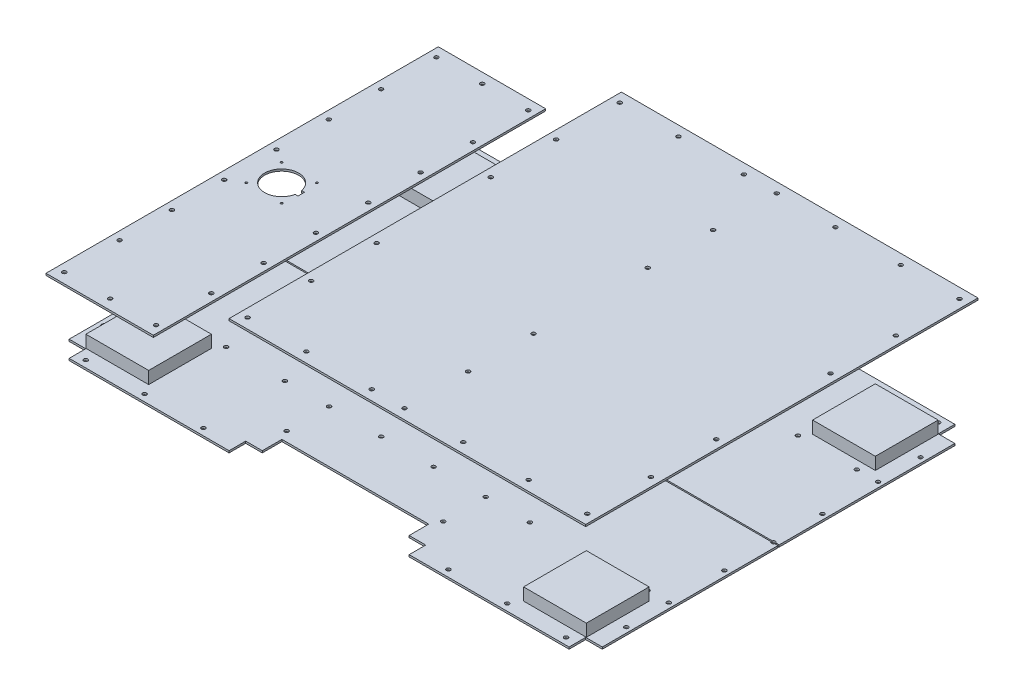
SolidWorks part; units mm, degrees
material "1060 Alloy"
ref_plane "Front Plane" through (0, 0, 0) normal (0, 0, 1) x (1, 0, 0)
ref_plane "Top Plane" through (0, 0, 0) normal (0, 1, 0) x (1, 0, 0)
ref_plane "Right Plane" through (0, 0, 0) normal (1, 0, 0) x (0, 0, -1)
sketch "Sketch2" plane through (0, 422.0595, 0) normal (0, 1, 0) x (1, 0, 0)
  line L0 (436.2951, -933.6952) -> (410.8951, -933.6952) construction
  line L9 (436.2951, -933.6952) -> (410.8951, -933.6952) construction
  line L11 (196.2951, -933.6952) -> (196.2951, -903.6952) construction
  line L19 (196.2951, -834.4952) -> (196.2951, -933.6952) construction
  line L21 (196.2951, -903.6952) -> (410.8951, -903.6952) construction
  line L22 (410.8951, -933.6952) -> (410.8951, -834.4952) construction
  line L72 (410.8951, -903.6952) -> (410.8951, -933.6952) construction
  line L73 (436.2951, -959.0952) -> (436.2951, -933.6952) construction
  line L76 (690.8951, -959.0952) -> (436.2951, -959.0952) construction
  line L78 (690.8951, -933.6952) -> (690.8951, -959.0952) construction
  line L79 (410.8951, -384.4952) -> (436.2951, -384.4952) construction
  line L80 (436.2951, -384.4952) -> (436.2951, -359.0952) construction
  line L81 (436.2951, -359.0952) -> (690.8951, -359.0952) construction
  line L82 (436.2951, -959.0952) -> (436.2951, -933.6952) construction
  line L83 (690.8951, -959.0952) -> (436.2951, -959.0952) construction
  line L84 (690.8951, -933.6952) -> (690.8951, -959.0952) construction
  line L85 (690.8951, -359.0952) -> (690.8951, -384.4952) construction
  line L86 (690.8951, -384.4952) -> (716.2951, -384.4952) construction
  line L87 (716.2951, -384.4952) -> (716.2951, -933.6952) construction
  line L88 (716.2951, -933.6952) -> (690.8951, -933.6952) construction
  line L89 (410.8951, -384.4952) -> (436.2951, -384.4952) construction
  line L90 (436.2951, -384.4952) -> (436.2951, -359.0952) construction
  line L91 (436.2951, -359.0952) -> (690.8951, -359.0952) construction
  line L92 (690.8951, -359.0952) -> (690.8951, -384.4952) construction
  line L93 (690.8951, -384.4952) -> (716.2951, -384.4952) construction
  line L94 (716.2951, -384.4952) -> (716.2951, -658.0952) construction
  line L95 (716.2951, -933.6952) -> (690.8951, -933.6952) construction
  line L96 (196.2951, -933.6952) -> (170.8951, -933.6952) construction
  line L97 (170.8951, -933.6952) -> (170.8951, -959.0952) construction
  line L98 (170.8951, -959.0952) -> (-83.7049, -959.0952) construction
  line L99 (-83.7049, -959.0952) -> (-83.7049, -933.6952) construction
  line L100 (-83.7049, -933.6952) -> (-109.1049, -933.6952) construction
  line L101 (-109.1049, -933.6952) -> (-109.1049, -384.4952) construction
  line L102 (-109.1049, -384.4952) -> (-83.7049, -384.4952) construction
  line L103 (-83.7049, -384.4952) -> (-83.7049, -359.0952) construction
  line L104 (-83.7049, -359.0952) -> (170.8951, -359.0952) construction
  line L105 (170.8951, -359.0952) -> (170.8951, -384.4952) construction
  line L106 (170.8951, -384.4952) -> (196.2951, -384.4952) construction
  line L107 (196.2951, -933.6952) -> (170.8951, -933.6952) construction
  line L108 (170.8951, -933.6952) -> (170.8951, -959.0952) construction
  line L109 (170.8951, -959.0952) -> (-83.7049, -959.0952) construction
  line L110 (-83.7049, -959.0952) -> (-83.7049, -933.6952) construction
  line L111 (-83.7049, -933.6952) -> (-109.1049, -933.6952) construction
  line L112 (-109.1049, -933.6952) -> (-109.1049, -660.0952) construction
  line L113 (-109.1049, -384.4952) -> (-83.7049, -384.4952) construction
  line L114 (-83.7049, -384.4952) -> (-83.7049, -359.0952) construction
  line L115 (-83.7049, -359.0952) -> (170.8951, -359.0952) construction
  line L116 (170.8951, -359.0952) -> (170.8951, -384.4952) construction
  line L117 (170.8951, -384.4952) -> (196.2951, -384.4952) construction
  line L118 (716.2951, -659.0952) -> (-109.1049, -659.0952) construction
  line L119 (196.2951, -384.4952) -> (196.2951, -414.4952) construction
  line L120 (196.2951, -384.4952) -> (196.2951, -483.6952) construction
  line L121 (196.2951, -414.4952) -> (410.8951, -414.4952) construction
  line L122 (410.8951, -483.6952) -> (410.8951, -384.4952) construction
  line L123 (410.8951, -414.4952) -> (410.8951, -384.4952) construction
  line L124 (716.2951, -658.0952) -> (-109.1049, -658.0952) construction
  line L125 (716.2951, -660.0952) -> (-109.1049, -660.0952) construction
  line L126 (716.2951, -660.0952) -> (716.2951, -933.6952) construction
  line L127 (-109.1049, -658.0952) -> (-109.1049, -384.4952) construction
  line L128 (711.2951, -660.0952) -> (711.2951, -928.6952)
  line L129 (711.2951, -928.6952) -> (685.8951, -928.6952)
  line L130 (685.8951, -928.6952) -> (685.8951, -954.0952)
  line L131 (685.8951, -954.0952) -> (441.2951, -954.0952)
  line L132 (441.2951, -954.0952) -> (441.2951, -928.6952)
  line L133 (441.2951, -928.6952) -> (415.8951, -928.6952)
  line L134 (415.8951, -898.6952) -> (415.8951, -928.6952)
  line L135 (191.2951, -898.6952) -> (415.8951, -898.6952)
  line L136 (191.2951, -928.6952) -> (191.2951, -898.6952)
  line L137 (191.2951, -928.6952) -> (165.8951, -928.6952)
  line L138 (165.8951, -928.6952) -> (165.8951, -954.0952)
  line L139 (165.8951, -954.0952) -> (-78.7049, -954.0952)
  line L140 (-78.7049, -954.0952) -> (-78.7049, -928.6952)
  line L141 (-78.7049, -928.6952) -> (-104.1049, -928.6952)
  line L142 (-104.1049, -928.6952) -> (-104.1049, -660.0952)
  line L143 (-104.1049, -658.0952) -> (-104.1049, -389.4952)
  line L144 (-104.1049, -389.4952) -> (-78.7049, -389.4952)
  line L145 (-78.7049, -389.4952) -> (-78.7049, -364.0952)
  line L146 (-78.7049, -364.0952) -> (165.8951, -364.0952)
  line L147 (165.8951, -364.0952) -> (165.8951, -389.4952)
  line L148 (165.8951, -389.4952) -> (191.2951, -389.4952)
  line L149 (191.2951, -389.4952) -> (191.2951, -419.4952)
  line L150 (191.2951, -419.4952) -> (415.8951, -419.4952)
  line L151 (415.8951, -419.4952) -> (415.8951, -389.4952)
  line L152 (415.8951, -389.4952) -> (441.2951, -389.4952)
  line L153 (441.2951, -389.4952) -> (441.2951, -364.0952)
  line L154 (441.2951, -364.0952) -> (685.8951, -364.0952)
  line L155 (685.8951, -364.0952) -> (685.8951, -389.4952)
  line L156 (685.8951, -389.4952) -> (711.2951, -389.4952)
  line L157 (711.2951, -389.4952) -> (711.2951, -658.0952)
  line L158 (-104.1049, -660.0952) -> (711.2951, -660.0952)
  line L159 (711.2951, -658.0952) -> (-104.1049, -658.0952)
  circle A0 centre (703.3951, -434.0952) radius 3 construction
  circle A1 centre (703.3951, -499.0952) radius 3 construction
  circle A2 centre (183.7951, -884.0952) radius 3 construction
  circle A3 centre (183.7951, -819.0952) radius 3 construction
  circle A5 centre (703.3951, -499.0952) radius 3
  circle A6 centre (703.3951, -434.0952) radius 3
  circle A7 centre (703.3951, -819.0952) radius 3 construction
  circle A8 centre (703.3951, -734.0952) radius 3 construction
  circle A9 centre (703.3951, -659.0952) radius 3 construction
  circle A10 centre (703.3951, -584.0952) radius 3 construction
  circle A11 centre (703.3951, -819.0952) radius 3
  circle A12 centre (703.3951, -734.0952) radius 3
  circle A13 centre (703.3951, -659.0952) radius 3
  circle A14 centre (703.3951, -584.0952) radius 3
  circle A15 centre (703.3951, -884.0952) radius 3 construction
  circle A16 centre (703.3951, -884.0952) radius 3
  circle A17 centre (116.2951, -943.6952) radius 3 construction
  circle A18 centre (490.8951, -943.6952) radius 3 construction
  circle A19 centre (580.8951, -943.6952) radius 3 construction
  circle A20 centre (670.8951, -943.6952) radius 3 construction
  circle A21 centre (116.2951, -943.6952) radius 3
  circle A22 centre (490.8951, -943.6952) radius 3
  circle A23 centre (580.8951, -943.6952) radius 3
  circle A24 centre (670.8951, -943.6952) radius 3
  circle A25 centre (26.2951, -943.6952) radius 3 construction
  circle A26 centre (26.2951, -943.6952) radius 3
  circle A27 centre (-63.7049, -943.6952) radius 3 construction
  circle A28 centre (-63.7049, -943.6952) radius 3
  circle A29 centre (-63.7049, -819.0952) radius 3 construction
  circle A30 centre (-96.2049, -884.0952) radius 3 construction
  circle A31 centre (-63.7049, -819.0952) radius 3
  circle A32 centre (-96.2049, -884.0952) radius 3
  circle A33 centre (-96.2049, -434.0952) radius 3 construction
  circle A34 centre (-96.2049, -584.0952) radius 3 construction
  circle A35 centre (-96.2049, -659.0952) radius 3 construction
  circle A36 centre (-96.2049, -734.0952) radius 3 construction
  circle A37 centre (-96.2049, -819.0952) radius 3 construction
  circle A38 centre (-96.2049, -434.0952) radius 3
  circle A39 centre (-96.2049, -584.0952) radius 3
  circle A40 centre (-96.2049, -659.0952) radius 3
  circle A41 centre (-96.2049, -734.0952) radius 3
  circle A42 centre (-96.2049, -819.0952) radius 3
  circle A43 centre (-96.2049, -499.0952) radius 3 construction
  circle A44 centre (26.2951, -499.0952) radius 3 construction
  circle A45 centre (-63.7049, -499.0952) radius 3 construction
  circle A46 centre (26.2951, -499.0952) radius 3
  circle A47 centre (-63.7049, -499.0952) radius 3
  circle A48 centre (-96.2049, -499.0952) radius 3
  circle A49 centre (116.2951, -499.0952) radius 3 construction
  circle A50 centre (116.2951, -499.0952) radius 3
  circle A51 centre (-63.7049, -374.4952) radius 3 construction
  circle A52 centre (26.2951, -374.4952) radius 3 construction
  circle A53 centre (116.2951, -374.4952) radius 3 construction
  circle A54 centre (-63.7049, -374.4952) radius 3
  circle A55 centre (26.2951, -374.4952) radius 3
  circle A56 centre (116.2951, -374.4952) radius 3
  circle A57 centre (183.7951, -584.0952) radius 3 construction
  circle A58 centre (183.7951, -499.0952) radius 3 construction
  circle A59 centre (183.7951, -434.0952) radius 3 construction
  circle A60 centre (183.7951, -584.0952) radius 3
  circle A61 centre (183.7951, -499.0952) radius 3
  circle A62 centre (183.7951, -434.0952) radius 3
  circle A63 centre (183.7951, -659.0952) radius 3 construction
  circle A64 centre (183.7951, -659.0952) radius 3
  circle A65 centre (183.7951, -734.0952) radius 3 construction
  circle A66 centre (183.7951, -734.0952) radius 3
  circle A67 centre (263.5951, -819.0952) radius 3 construction
  circle A68 centre (183.7951, -884.0952) radius 3
  circle A69 centre (183.7951, -819.0952) radius 3
  circle A70 centre (263.5951, -819.0952) radius 3
  circle A71 centre (343.5951, -819.0952) radius 3 construction
  circle A72 centre (343.5951, -819.0952) radius 3
  circle A73 centre (423.3951, -884.0952) radius 3 construction
  circle A74 centre (423.3951, -819.0952) radius 3 construction
  circle A75 centre (490.8951, -819.0952) radius 3 construction
  circle A76 centre (423.3951, -734.0952) radius 3 construction
  circle A77 centre (423.3951, -884.0952) radius 3
  circle A78 centre (423.3951, -819.0952) radius 3
  circle A79 centre (490.8951, -819.0952) radius 3
  circle A80 centre (423.3951, -734.0952) radius 3
  circle A81 centre (423.3951, -659.0952) radius 3 construction
  circle A82 centre (423.3951, -659.0952) radius 3
  circle A83 centre (670.8951, -819.0952) radius 3 construction
  circle A84 centre (580.8951, -819.0952) radius 3 construction
  circle A85 centre (670.8951, -819.0952) radius 3
  circle A86 centre (580.8951, -819.0952) radius 3
  circle A87 centre (490.8951, -374.4952) radius 3 construction
  circle A88 centre (580.8951, -374.4952) radius 3 construction
  circle A89 centre (670.8951, -374.4952) radius 3 construction
  circle A90 centre (490.8951, -374.4952) radius 3
  circle A91 centre (580.8951, -374.4952) radius 3
  circle A92 centre (670.8951, -374.4952) radius 3
  circle A93 centre (423.3951, -584.0952) radius 3 construction
  circle A94 centre (423.3951, -584.0952) radius 3
  circle A95 centre (423.3951, -434.0952) radius 3 construction
  circle A96 centre (423.3951, -434.0952) radius 3
  circle A97 centre (423.3951, -499.0952) radius 3 construction
  circle A98 centre (423.3951, -499.0952) radius 3
  circle A99 centre (343.5951, -499.0952) radius 3 construction
  circle A100 centre (343.5951, -499.0952) radius 3
  circle A101 centre (263.5951, -499.0952) radius 3 construction
  circle A102 centre (263.5951, -499.0952) radius 3
  circle A103 centre (670.8951, -499.0952) radius 3 construction
  circle A104 centre (580.8951, -499.0952) radius 3 construction
  circle A105 centre (490.8951, -499.0952) radius 3 construction
  circle A106 centre (670.8951, -499.0952) radius 3
  circle A107 centre (580.8951, -499.0952) radius 3
  circle A108 centre (490.8951, -499.0952) radius 3
  circle A109 centre (116.2951, -819.0952) radius 3 construction
  circle A110 centre (26.2951, -819.0952) radius 3 construction
  circle A111 centre (116.2951, -819.0952) radius 3
  circle A112 centre (26.2951, -819.0952) radius 3
  point P56 (712.1088, -386.4469)
  point P57 (713.2951, -659.0952)
  point P72 (-106.1049, -387.4952)
  point P73 (-106.1049, -930.6952)
  point P88 (0, 0)
  point P90 (-109.1049, -658.0952)
  point P92 (-109.1049, -660.0952)
  dimension "D1" = 30
  dimension "D2" = 30
  dimension "D5" = 300
  dimension "D6" = 5
  dimension "D3" = 1
  dimension "D4" = 1
extrude "Boss-Extrude1" add sketch "Sketch2" along normal blind 3
sketch "Sketch4" plane through (0, 602.0595, 0) normal (0, 1, 0) x (1, 0, 0)
  line L0 (716.2951, -359.0952) -> (170.8951, -359.0952) construction
  line L1 (170.8951, -359.0952) -> (170.8951, -959.0952) construction
  line L2 (170.8951, -933.6952) -> (170.8951, -384.4952) construction
  line L3 (716.2951, -959.0952) -> (716.2951, -359.0952) construction
  line L4 (170.8951, -959.0952) -> (716.2951, -959.0952) construction
  line L5 (716.2951, -359.0952) -> (170.8951, -359.0952)
  line L6 (170.8951, -359.0952) -> (170.8951, -959.0952)
  line L7 (170.8951, -933.6952) -> (170.8951, -384.4952)
  line L8 (716.2951, -959.0952) -> (716.2951, -359.0952)
  line L9 (170.8951, -959.0952) -> (716.2951, -959.0952)
  line L10 (170.8951, -359.0952) -> (716.2951, -959.0952) construction
  line L11 (170.8951, -959.0952) -> (716.2951, -359.0952) construction
  line L12 (443.5951, -659.0952) -> (716.2951, -659.0952) construction
  circle A1 centre (613.5951, -943.6952) radius 3 construction
  circle A2 centre (703.3951, -943.6952) radius 3 construction
  circle A3 centre (513.5951, -943.6952) radius 3 construction
  circle A4 centre (703.3951, -846.3952) radius 3 construction
  circle A5 centre (703.3951, -746.3952) radius 3 construction
  circle A6 centre (423.7951, -943.6952) radius 3 construction
  circle A7 centre (423.7951, -846.3952) radius 3 construction
  circle A8 centre (373.5951, -943.6952) radius 3 construction
  circle A9 centre (273.5951, -943.6952) radius 3 construction
  circle A10 centre (183.7951, -943.6952) radius 3 construction
  circle A11 centre (183.7951, -746.3952) radius 3 construction
  circle A12 centre (183.7951, -846.3952) radius 3 construction
  circle A13 centre (423.7951, -746.3952) radius 3 construction
  circle A14 centre (423.7951, -746.3952) radius 3
  circle A15 centre (183.7951, -846.3952) radius 3
  circle A16 centre (183.7951, -746.3952) radius 3
  circle A17 centre (183.7951, -943.6952) radius 3
  circle A18 centre (273.5951, -943.6952) radius 3
  circle A19 centre (373.5951, -943.6952) radius 3
  circle A20 centre (423.7951, -846.3952) radius 3
  circle A21 centre (423.7951, -943.6952) radius 3
  circle A22 centre (703.3951, -746.3952) radius 3
  circle A23 centre (703.3951, -846.3952) radius 3
  circle A24 centre (513.5951, -943.6952) radius 3
  circle A25 centre (703.3951, -943.6952) radius 3
  circle A26 centre (613.5951, -943.6952) radius 3
  circle A40 centre (613.5951, -374.4952) radius 3
  circle A41 centre (703.3951, -374.4952) radius 3
  circle A42 centre (513.5951, -374.4952) radius 3
  circle A43 centre (703.3951, -471.7952) radius 3
  circle A44 centre (703.3951, -571.7952) radius 3
  circle A45 centre (423.7951, -374.4952) radius 3
  circle A46 centre (423.7951, -471.7952) radius 3
  circle A47 centre (373.5951, -374.4952) radius 3
  circle A48 centre (273.5951, -374.4952) radius 3
  circle A49 centre (183.7951, -374.4952) radius 3
  circle A50 centre (183.7951, -571.7952) radius 3
  circle A51 centre (183.7951, -471.7952) radius 3
  circle A52 centre (423.7951, -571.7952) radius 3
extrude "Boss-Extrude2" add sketch "Sketch4" along normal blind 3 separate body contours L5 L6 L9 L8 | A49 | A48 | A47 | A46 | A51 | A50 | A52 | A45 | A42 | A40 | A41 | A43 | A44 | A22 | A14 | A16 | A15 | A18 | A19 | A20 | A21 | A24 | A26 | A23 | A25 | A17
sketch "Sketch6" plane through (0, 522.0595, 0) normal (0, 1, 0) x (1, 0, 0)
  line L0 (-109.1049, -959.0952) -> (-109.1049, -359.0952) construction
  line L1 (55.0951, -384.4952) -> (55.0951, -933.6952) construction
  line L2 (-109.1049, -959.0952) -> (-109.1049, -359.0952)
  line L3 (55.0951, -384.4952) -> (55.0951, -933.6952)
  line L4 (55.0951, -933.6952) -> (55.0951, -959.0952)
  line L5 (170.8951, -959.0952) -> (-109.1049, -959.0952) construction
  line L6 (55.0951, -959.0952) -> (-109.1049, -959.0952)
  line L7 (55.0951, -384.4952) -> (55.0951, -359.0952)
  line L8 (170.8951, -359.0952) -> (-109.1049, -359.0952) construction
  line L9 (55.0951, -359.0952) -> (-109.1049, -359.0952)
  line L10 (55.0951, -659.0952) -> (-109.1049, -659.0952) construction
  circle A0 centre (-96.6049, -943.6952) radius 3 construction
  circle A1 centre (-26.3999, -943.6952) radius 3 construction
  circle A2 centre (43.7951, -943.6952) radius 3 construction
  circle A3 centre (-96.6049, -943.6952) radius 3
  circle A4 centre (-26.3999, -943.6952) radius 3
  circle A5 centre (43.7951, -943.6952) radius 3
  circle A6 centre (-96.6049, -859.0952) radius 3 construction
  circle A7 centre (43.7951, -859.0952) radius 3 construction
  circle A8 centre (-96.6049, -859.0952) radius 3
  circle A9 centre (43.7951, -859.0952) radius 3
  circle A10 centre (43.7951, -699.0952) radius 3 construction
  circle A11 centre (-96.6049, -699.0952) radius 3 construction
  circle A12 centre (43.7951, -779.0952) radius 3 construction
  circle A13 centre (-96.6049, -779.0952) radius 3 construction
  circle A14 centre (43.7951, -699.0952) radius 3
  circle A15 centre (-96.6049, -699.0952) radius 3
  circle A16 centre (43.7951, -779.0952) radius 3
  circle A17 centre (-96.6049, -779.0952) radius 3
  circle A27 centre (-96.6049, -619.0952) radius 3
  circle A28 centre (-96.6049, -539.0952) radius 3
  circle A29 centre (43.7951, -539.0952) radius 3
  circle A30 centre (43.7951, -619.0952) radius 3
  circle A31 centre (43.7951, -459.0952) radius 3
  circle A32 centre (-96.6049, -459.0952) radius 3
  circle A33 centre (43.7951, -374.4952) radius 3
  circle A34 centre (-26.3999, -374.4952) radius 3
  circle A35 centre (-96.6049, -374.4952) radius 3
extrude "Boss-Extrude3" add sketch "Sketch6" along normal blind 3 separate body
sketch "Sketch9" plane through (0, 525.0595, 0) normal (0, 1, 0) x (1, 0, 0)
  line L0 (-48.7049, -659.0952) -> (-22.7049, -659.0952) construction
  line L1 (-48.7049, -654.0952) -> (-22.7049, -654.0952) construction
  line L2 (-48.7049, -664.0952) -> (-22.7049, -664.0952) construction
  line L3 (-23.1902, -654.0952) -> (-18.6902, -654.0952)
  line L4 (-18.6902, -654.0952) -> (-18.6902, -664.0952)
  line L5 (-18.6902, -664.0952) -> (-23.1902, -664.0952)
  line L6 (-109.1049, -359.0952) -> (-109.1049, -959.0952) construction
  line L7 (-109.1049, -959.0952) -> (55.0951, -959.0952) construction
  arc A0 (-23.1902, -654.0952) -> (-23.1902, -664.0952) centre (-48.7049, -659.0952) ccw
  dimension "D1" = 26
  dimension "D4" = 300
  dimension "D5" = 90.4147
  dimension "D2" = 60.4
  dimension "D3" = 85.9147
extrude "Cut-Extrude1" cut sketch "Sketch9" against normal up to next (3 mm away)
sketch "Sketch10" plane through (0, 525.0595, 0) normal (0, 1, 0) x (1, 0, 0)
  line L0 (-109.1049, -359.0952) -> (-109.1049, -959.0952) construction
  line L1 (-109.1049, -959.0952) -> (55.0951, -959.0952) construction
  circle A0 centre (-21.7049, -632.0952) radius 1.6
  circle A1 centre (-21.7049, -686.0952) radius 1.6
  circle A2 centre (-75.7049, -632.0952) radius 1.6
  circle A3 centre (-75.7049, -686.0952) radius 1.6
  dimension "D1" = 3.2
  dimension "D2" = 33.4
  dimension "D3" = 87.4
  dimension "D4" = 273
  dimension "D5" = 327
extrude "Cut-Extrude4" cut sketch "Sketch10" against normal up to next (3 mm away)
sketch "Sketch13" plane through (0, 422.0595, 0) normal (0, -1, 0) x (1, 0, 0)
  line L0 (165.8951, 954.0952) -> (-78.7049, 954.0952) construction
  line L7 (303.5951, 901.0952) -> (303.5951, 417.0952) construction
  line L26 (303.5951, 659.0952) -> (712.9729, 659.0952) construction
  line L34 (-76.1049, 925.0952) -> (-76.1049, 835.0952)
  line L35 (13.8951, 925.0952) -> (13.8951, 835.0952)
  line L36 (-76.1049, 835.0952) -> (13.8951, 835.0952)
  line L37 (-76.1049, 925.0952) -> (13.8951, 925.0952)
  line L40 (-104.1049, 928.6952) -> (-104.1049, 660.0952) construction
  line L41 (-76.1049, 393.0952) -> (13.8951, 393.0952)
  line L42 (-76.1049, 483.0952) -> (13.8951, 483.0952)
  line L43 (13.8951, 393.0952) -> (13.8951, 483.0952)
  line L44 (-76.1049, 393.0952) -> (-76.1049, 483.0952)
  line L45 (683.2951, 393.0952) -> (683.2951, 483.0952)
  line L46 (593.2951, 393.0952) -> (593.2951, 483.0952)
  line L47 (683.2951, 483.0952) -> (593.2951, 483.0952)
  line L48 (683.2951, 393.0952) -> (593.2951, 393.0952)
  line L49 (683.2951, 925.0952) -> (593.2951, 925.0952)
  line L50 (683.2951, 835.0952) -> (593.2951, 835.0952)
  line L51 (593.2951, 925.0952) -> (593.2951, 835.0952)
  line L52 (683.2951, 925.0952) -> (683.2951, 835.0952)
  dimension "D1" = 29
  dimension "D2" = 90
  dimension "D3" = 90
  dimension "D4" = 28
  dimension "D5" = 118
extrude "Cut-Extrude6" cut sketch "Sketch13" along direction (0, 1, 0) on the side against the normal up to surface (3 mm away)
sketch "Sketch15" plane through (0, 422.0595, 0) normal (0, -1, 0) x (1, 0, 0)
  line L0 (-76.1049, 393.0952) -> (13.8951, 393.0952) construction
  line L1 (-76.1049, 483.0952) -> (-76.1049, 393.0952) construction
  line L2 (13.8951, 393.0952) -> (13.8951, 483.0952) construction
  line L3 (13.8951, 483.0952) -> (-76.1049, 483.0952) construction
  line L13 (13.8951, 925.0952) -> (-76.1049, 925.0952) construction
  line L15 (-76.1049, 925.0952) -> (-76.1049, 835.0952) construction
  line L41 (13.8951, 835.0952) -> (13.8951, 925.0952) construction
  line L75 (-76.1049, 835.0952) -> (13.8951, 835.0952) construction
  line L78 (-76.1049, 393.0952) -> (13.8951, 393.0952) construction
  line L88 (-76.1049, 483.0952) -> (-76.1049, 393.0952) construction
  line L89 (13.8951, 393.0952) -> (13.8951, 483.0952) construction
  line L90 (13.8951, 483.0952) -> (-76.1049, 483.0952) construction
  line L91 (13.8951, 925.0952) -> (-76.1049, 925.0952) construction
  line L92 (-76.1049, 925.0952) -> (-76.1049, 835.0952) construction
  line L93 (13.8951, 835.0952) -> (13.8951, 925.0952) construction
  line L94 (-76.1049, 835.0952) -> (13.8951, 835.0952) construction
  line L95 (683.2951, 835.0952) -> (683.2951, 925.0952) construction
  line L96 (593.2951, 925.0952) -> (593.2951, 835.0952) construction
  line L97 (593.2951, 835.0952) -> (683.2951, 835.0952) construction
  line L98 (683.2951, 925.0952) -> (593.2951, 925.0952) construction
  line L99 (593.2951, 393.0952) -> (683.2951, 393.0952) construction
  line L100 (683.2951, 393.0952) -> (683.2951, 483.0952) construction
  line L101 (683.2951, 483.0952) -> (593.2951, 483.0952) construction
  line L102 (593.2951, 483.0952) -> (593.2951, 393.0952) construction
  line L103 (593.2951, 393.0952) -> (683.2951, 393.0952) construction
  line L104 (593.2951, 483.0952) -> (593.2951, 393.0952) construction
  line L105 (683.2951, 483.0952) -> (593.2951, 483.0952) construction
  line L106 (683.2951, 393.0952) -> (683.2951, 483.0952) construction
  line L107 (683.2951, 835.0952) -> (683.2951, 925.0952) construction
  line L108 (683.2951, 925.0952) -> (593.2951, 925.0952) construction
  line L109 (593.2951, 835.0952) -> (683.2951, 835.0952) construction
  line L110 (593.2951, 925.0952) -> (593.2951, 835.0952) construction
  line L111 (-79.1049, 390.0952) -> (16.8951, 390.0952)
  line L112 (16.8951, 390.0952) -> (16.8951, 486.0952)
  line L113 (16.8951, 486.0952) -> (-79.1049, 486.0952)
  line L114 (-79.1049, 486.0952) -> (-79.1049, 390.0952)
  line L115 (16.8951, 928.0952) -> (-79.1049, 928.0952)
  line L116 (-79.1049, 928.0952) -> (-79.1049, 832.0952)
  line L117 (-79.1049, 832.0952) -> (16.8951, 832.0952)
  line L118 (16.8951, 832.0952) -> (16.8951, 928.0952)
  line L119 (590.2951, 390.0952) -> (686.2951, 390.0952)
  line L120 (686.2951, 390.0952) -> (686.2951, 486.0952)
  line L121 (686.2951, 486.0952) -> (590.2951, 486.0952)
  line L122 (590.2951, 486.0952) -> (590.2951, 390.0952)
  line L123 (686.2951, 832.0952) -> (686.2951, 928.0952)
  line L136 (686.2951, 928.0952) -> (590.2951, 928.0952)
  line L137 (590.2951, 928.0952) -> (590.2951, 832.0952)
  line L138 (590.2951, 832.0952) -> (686.2951, 832.0952)
  dimension "D1" = 3
extrude "Boss-Extrude4" add sketch "Sketch15" against normal blind 18.8 from surface at -3 starting at face at (-31.1049, 425.0595, 438.0952)
sketch "Sketch16" plane through (0, 422.0595, 0) normal (0, -1, 0) x (1, 0, 0)
  line L4 (683.2951, 393.0952) -> (683.2951, 483.0952) construction
  line L5 (593.2951, 393.0952) -> (683.2951, 393.0952) construction
  line L8 (-76.1049, 925.0952) -> (-76.1049, 835.0952)
  line L9 (-76.1049, 835.0952) -> (13.8951, 835.0952)
  line L10 (13.8951, 835.0952) -> (13.8951, 925.0952)
  line L11 (13.8951, 925.0952) -> (-76.1049, 925.0952)
  line L16 (13.8951, 393.0952) -> (13.8951, 483.0952)
  line L17 (13.8951, 483.0952) -> (-76.1049, 483.0952)
  line L18 (-76.1049, 483.0952) -> (-76.1049, 393.0952)
  line L19 (-76.1049, 393.0952) -> (13.8951, 393.0952)
  line L24 (683.2951, 925.0952) -> (593.2951, 925.0952)
  line L25 (593.2951, 925.0952) -> (593.2951, 835.0952)
  line L26 (593.2951, 835.0952) -> (683.2951, 835.0952)
  line L27 (683.2951, 835.0952) -> (683.2951, 925.0952)
  line L28 (683.2951, 393.0952) -> (683.2951, 483.0952)
  line L29 (683.2951, 483.0952) -> (593.2951, 483.0952)
  line L30 (593.2951, 483.0952) -> (593.2951, 393.0952)
  line L31 (593.2951, 393.0952) -> (683.2951, 393.0952)
  dimension "D1" = 90
  dimension "D2" = 669.4
  dimension "D3" = 442
extrude "Cut-Extrude7" cut sketch "Sketch16" against normal offset from surface (18.8 mm away) 3 up to face at (-31.1049, 443.8595, 438.0952)
